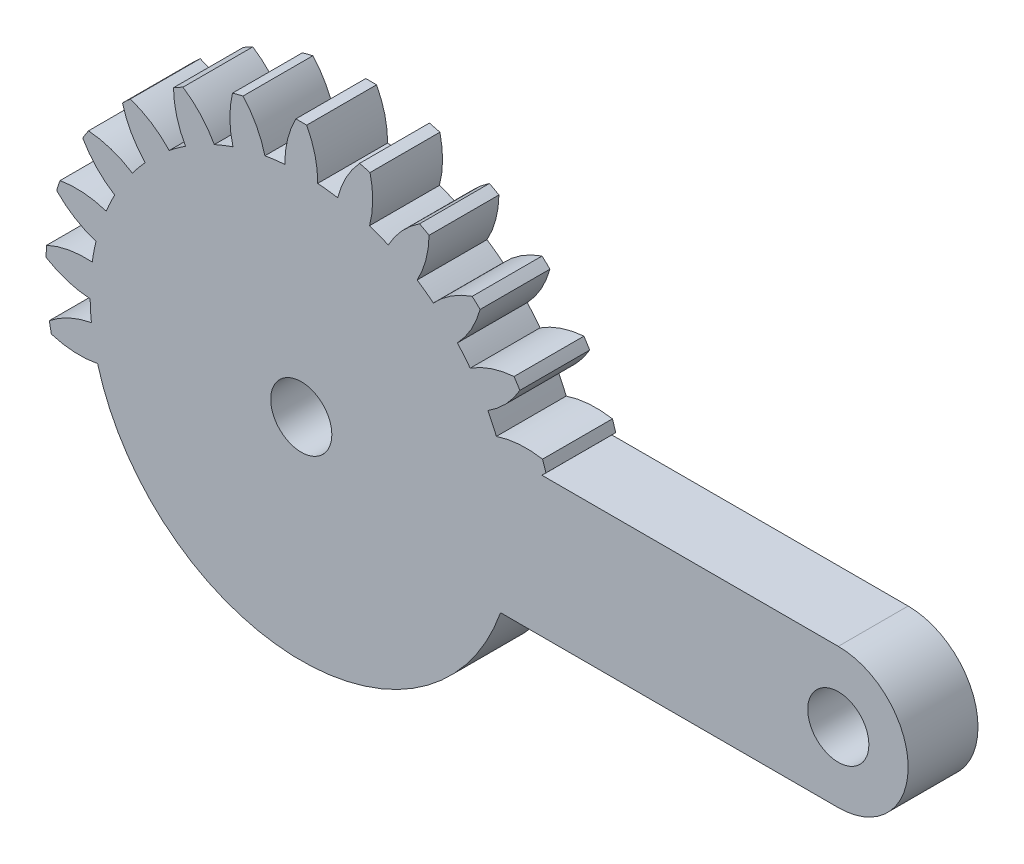
SolidWorks part; units mm, degrees
ref_plane "Front Plane" through (0, 0, 0) normal (0, 0, 1) x (1, 0, 0)
ref_plane "Top Plane" through (0, 0, 0) normal (0, 1, 0) x (1, 0, 0)
ref_plane "Right Plane" through (0, 0, 0) normal (1, 0, 0) x (0, 0, -1)
sketch "Sketch1" plane through (0, 0, 0) normal (0, 0, 1) x (1, 0, 0)
  line L0 (0, 0) -> (0, 14.63) construction
  line L1 (0, 0) -> (21.7469, 0) construction
  line L2 (11.4091, 4) -> (30.75, 4)
  line L3 (30.75, -4) -> (11.4091, -4)
  circle A0 centre (0, 0) radius 1.75
  circle A1 centre (0, 0) radius 12.09
  circle A2 centre (0, 0) radius 14.63
  arc A3 (0.31, 14.6267) -> (0.9431, 12.0532) centre (-4.4568, 12.0894) cw
  arc A4 (-0.31, 14.6267) -> (-0.9431, 12.0532) centre (4.4568, 12.0894) ccw
  arc A5 (3.3373, 14.2443) -> (2.084, 11.909) centre (7.3233, 10.6013) ccw
  arc A6 (3.9378, 14.0901) -> (3.911, 11.4399) centre (-1.3102, 12.818) cw
  arc A7 (6.7748, 12.9668) -> (4.9802, 11.0166) centre (9.7296, 8.447) ccw
  arc A8 (7.3181, 12.6681) -> (6.6331, 10.1079) centre (1.9186, 12.7411) cw
  arc A9 (9.7867, 10.8746) -> (7.5635, 9.432) centre (11.5246, 5.7619) ccw
  arc A10 (10.2387, 10.4502) -> (8.9384, 8.1408) centre (5.0269, 11.8637) cw
  arc A11 (12.1836, 8.0991) -> (9.6715, 7.2547) centre (12.5955, 2.7149) ccw
  arc A12 (12.5159, 7.5756) -> (10.6822, 5.6621) centre (7.8194, 10.2408) cw
  arc A13 (13.815, 4.8147) -> (11.1718, 4.6216) centre (12.875, -0.5028) ccw
  arc A14 (14.0066, 4.2251) -> (11.7547, 2.8277) centre (10.1205, 7.9745) cw
  arc A15 (14.5784, 1.2278) -> (11.9702, 1.6981) centre (12.3454, -3.6889) ccw
  arc A16 (14.6173, 0.609) -> (12.0886, -0.1844) centre (11.7857, 5.2071) cw
  arc A17 (14.4257, -2.4363) -> (12.0164, -1.3321) centre (11.0402, -6.6432) ccw
  arc A18 (14.3095, -3.0453) -> (11.6629, -3.1849) centre (12.7104, 2.1125) cw
  arc A19 (13.3666, -5.9473) -> (11.3076, -4.2786) centre (9.0412, -9.18) ccw
  arc A20 (13.1027, -6.5082) -> (10.5045, -5.9853) centre (12.8364, -1.1148) cw
  arc A21 (11.4677, -9.0846) -> (9.8883, -6.9563) centre (6.4742, -11.1401) ccw
  arc A22 (11.0725, -9.5623) -> (8.686, -8.4096) centre (12.1559, -4.2721) cw
  arc A23 (8.8482, -11.651) -> (7.8477, -9.1969) centre (3.5004, -12.4002) ccw
  arc A24 (8.3466, -12.0155) -> (6.3217, -10.3056) centre (10.7116, -7.1609) cw
  arc A25 (5.6727, -13.4855) -> (5.3139, -10.8596) centre (0.3066, -12.8811) ccw
  arc A26 (5.0962, -13.7137) -> (3.5602, -11.5539) centre (8.5942, -9.5998) cw
  arc A27 (2.1408, -14.4725) -> (2.4463, -11.8399) centre (-2.9064, -12.5527) ccw
  arc A28 (1.5257, -14.5502) -> (0.575, -12.0763) centre (5.9368, -11.4355) cw
  arc A29 (-1.5257, -14.5502) -> (-0.575, -12.0763) centre (-5.9368, -11.4355) ccw
  arc A30 (-2.1408, -14.4725) -> (-2.4463, -11.8399) centre (2.9064, -12.5527) cw
  arc A31 (-5.0962, -13.7137) -> (-3.5602, -11.5539) centre (-8.5942, -9.5998) ccw
  arc A32 (-5.6727, -13.4855) -> (-5.3139, -10.8596) centre (-0.3066, -12.8811) cw
  arc A33 (-8.3466, -12.0155) -> (-6.3217, -10.3056) centre (-10.7116, -7.1609) ccw
  arc A34 (-8.8482, -11.651) -> (-7.8477, -9.1969) centre (-3.5004, -12.4002) cw
  arc A35 (-11.0725, -9.5623) -> (-8.686, -8.4096) centre (-12.1559, -4.2721) ccw
  arc A36 (-11.4677, -9.0846) -> (-9.8883, -6.9563) centre (-6.4742, -11.1401) cw
  arc A37 (-13.1027, -6.5082) -> (-10.5045, -5.9853) centre (-12.8364, -1.1148) ccw
  arc A38 (-13.3666, -5.9473) -> (-11.3076, -4.2786) centre (-9.0412, -9.18) cw
  arc A39 (-14.3095, -3.0453) -> (-11.6629, -3.1849) centre (-12.7104, 2.1125) ccw
  arc A40 (-14.4257, -2.4363) -> (-12.0164, -1.3321) centre (-11.0402, -6.6432) cw
  arc A41 (-14.6173, 0.609) -> (-12.0886, -0.1844) centre (-11.7857, 5.2071) ccw
  arc A42 (-14.5784, 1.2278) -> (-11.9702, 1.6981) centre (-12.3454, -3.6889) cw
  arc A43 (-14.0066, 4.2251) -> (-11.7547, 2.8277) centre (-10.1205, 7.9745) ccw
  arc A44 (-13.815, 4.8147) -> (-11.1718, 4.6216) centre (-12.875, -0.5028) cw
  arc A45 (-12.5159, 7.5756) -> (-10.6822, 5.6621) centre (-7.8194, 10.2408) ccw
  arc A46 (-12.1836, 8.0991) -> (-9.6715, 7.2547) centre (-12.5955, 2.7149) cw
  arc A47 (-10.2387, 10.4502) -> (-8.9384, 8.1408) centre (-5.0269, 11.8637) ccw
  arc A48 (-9.7867, 10.8746) -> (-7.5635, 9.432) centre (-11.5246, 5.7619) cw
  arc A49 (-7.3181, 12.6681) -> (-6.6331, 10.1079) centre (-1.9186, 12.7411) ccw
  arc A50 (-6.7748, 12.9668) -> (-4.9802, 11.0166) centre (-9.7296, 8.447) cw
  arc A51 (30.75, 4) -> (30.75, -4) centre (30.75, 0) cw
  circle A52 centre (30.75, 0) radius 1.75
  arc A53 (-3.9378, 14.0901) -> (-3.911, 11.4399) centre (1.3102, 12.818) ccw
  arc A54 (-3.3373, 14.2443) -> (-2.084, 11.909) centre (-7.3233, 10.6013) cw
  point P153 (0, 0)
  dimension "D1" = 3.5
  dimension "D2" = 24.18
  dimension "D3" = 29.26
  dimension "D4" = 0.62
  dimension "D6" = 5.4
  dimension "D8" = 30.75
  dimension "D9" = 4
  dimension "D10" = 3.5
  dimension "D11" = 1.15
  dimension "D7" = 25
extrude "Boss-Extrude1" add sketch "Sketch1" along normal blind 4 contours A51 L2 A2 L3 A52 | A18 A2 A17 A1 | A2 A18 A1 L3 | A16 A2 A15 A1 | A14 L2 A1 | A14 A2 A13 A1 L2 | A12 A2 A11 A1 | A10 A2 A9 A1 | A17 A2 A16 A1 | A15 A2 L2 A14 A1 | A8 A2 A7 A1 | A6 A2 A5 A1 | A2 A4 A1 A3 | A54 A2 A53 A1 | A50 A2 A49 A1 | A48 A2 A47 A1 | A46 A2 A45 A1 | A44 A2 A43 A1 | A42 A2 A41 A1 | A40 A2 A39 A1 | A1 A3
